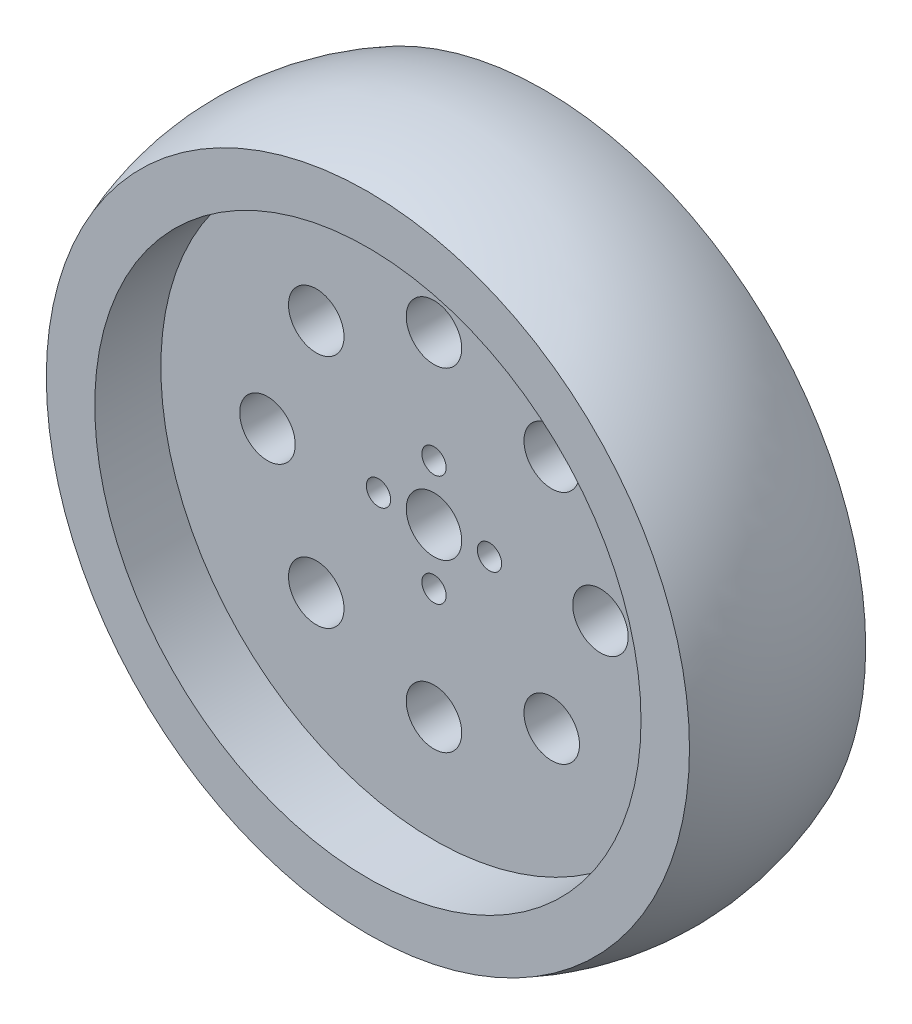
SolidWorks part; units mm, degrees
material "Nylon"
ref_plane "Front Plane" through (0, 0, 0) normal (0, 0, 1) x (1, 0, 0)
ref_plane "Top Plane" through (0, 0, 0) normal (0, 1, 0) x (1, 0, 0)
ref_plane "Right Plane" through (0, 0, 0) normal (1, 0, 0) x (0, 0, -1)
sketch "Sketch1" plane through (0, 0, 0) normal (0, 0, 1) x (1, 0, 0)
  circle A0 centre (0, 0) radius 44.45
  dimension "D1" = 88.9
extrude "Extrude1" add sketch "Sketch1" against normal blind 21.082
sketch "Sketch2" plane through (0, 0, 0) normal (0, 0, 1) x (1, 0, 0)
  circle A0 centre (0, 0) radius 39.37
  dimension "D1" = 78.74
extrude "Cut-Extrude1" cut sketch "Sketch2" against normal blind 7.366
sketch "Sketch3" plane through (0, 0, -21.082) normal (0, 0, -1) x (-1, 0, 0)
  circle A0 centre (0, 0) radius 39.37
  dimension "D1" = 78.74
extrude "Cut-Extrude2" cut sketch "Sketch3" against normal blind 7.366
sketch "Sketch4" plane through (0, 0, 0) normal (0, 0, 1) x (1, 0, 0)
  circle A0 centre (0, 0) radius 46.355
  dimension "D1" = 92.71
extrude "Extrude2" add sketch "Sketch4" along normal blind 2.159
sketch "Sketch5" plane through (0, 0, -21.082) normal (0, 0, -1) x (-1, 0, 0)
  circle A0 centre (0, 0) radius 46.355
  dimension "D1" = 92.71
extrude "Extrude3" add sketch "Sketch5" along normal blind 2.159
sketch "Sketch6" plane through (0, 0, 2.159) normal (0, 0, 1) x (1, 0, 0)
  circle A0 centre (0, 0) radius 39.37
  dimension "D1" = 78.74
extrude "Cut-Extrude3" cut sketch "Sketch6" against normal up to next
sketch "Sketch7" plane through (0, 0, -23.241) normal (0, 0, -1) x (-1, 0, 0)
  circle A0 centre (0, 0) radius 39.37
  dimension "D1" = 78.74
extrude "Cut-Extrude4" cut sketch "Sketch7" against normal up to next
sketch3d "3DSketch1"
  line L0 (0, 46.355, 2.159) -> (0, 46.355, 0)
  line L1 (0, 46.355, 0) -> (0, 44.4548, 0)
  line L2 (0, 44.4548, 0) -> (0, 44.45, -21.082)
  line L3 (0, 44.45, -21.082) -> (0, 46.355, -21.082)
  line L4 (0, 46.355, -21.082) -> (0, 46.355, -23.241)
  arc A0 (0, 46.355, 2.159) -> (0, 46.355, -23.241) centre (0, 14.5789, -10.541) cw
  circle A1 centre (0, 0, 2.159) radius 46.355 construction
  circle A2 centre (0, 0, -23.241) radius 46.355 construction
  circle A3 centre (0, 0, 0) radius 46.355 construction
  circle A4 centre (0, 0, -21.082) radius 44.45 construction
  circle A5 centre (0, 0, -21.082) radius 46.355 construction
  point P2 (-34.22, 14.5789, -10.541)
  point P7 (0, 0, 48.514)
  point P10 (0, 0, -69.596)
  point P13 (0, 0, 46.355)
  point P18 (0, 0, 23.368)
  point P22 (0, 0, -67.437)
sweep "Sweep1" add profiles "3DSketch1" path edge at (46.355, 0, 2.159)
sketch "Sketch8" plane through (0, 0, -7.366) normal (0, 0, 1) x (1, 0, 0)
  circle A0 centre (0, 0) radius 4
  circle A1 centre (0, 8) radius 1.75
  circle A2 centre (8, 0) radius 1.75
  circle A3 centre (0, -8) radius 1.75
  circle A4 centre (-8, 0) radius 1.75
  dimension "D1" = 3.5
  dimension "D2" = 3.5
  dimension "D3" = 3.5
  dimension "D4" = 3.5
  dimension "D5" = 8
  dimension "D6" = 8
  dimension "D7" = 8
  dimension "D8" = 8
  dimension "D9" = 8
extrude "Cut-Extrude5" cut sketch "Sketch8" against normal through all
sketch "Sketch9" plane through (0, 0, -7.366) normal (0, 0, 1) x (1, 0, 0)
  line L0 (0, 0) -> (43.6024, 43.6024) construction
  line L1 (0, 0) -> (-40.8772, -40.8772) construction
  line L2 (0, 0) -> (39.4677, -39.4677) construction
  line L3 (0, 0) -> (-45.1999, 45.1999) construction
  circle A0 centre (0, 24) radius 4
  circle A1 centre (24, 0) radius 4
  circle A2 centre (0, -24) radius 4
  circle A3 centre (-24, 0) radius 4
  circle A4 centre (16.9706, 16.9706) radius 4
  circle A5 centre (16.9706, -16.9706) radius 4
  circle A6 centre (-16.9706, -16.9706) radius 4
  circle A7 centre (-16.9706, 16.9706) radius 4
  dimension "D1" = 8
  dimension "D2" = 8
  dimension "D3" = 8
  dimension "D4" = 8
  dimension "D5" = 8
  dimension "D6" = 8
  dimension "D7" = 8
  dimension "D8" = 8
  dimension "D9" = 24
  dimension "D10" = 24
  dimension "D11" = 24
  dimension "D12" = 24
  dimension "D13" = 24
  dimension "D14" = 24
  dimension "D15" = 24
  dimension "D16" = 24
extrude "Cut-Extrude6" cut sketch "Sketch9" against normal through all
